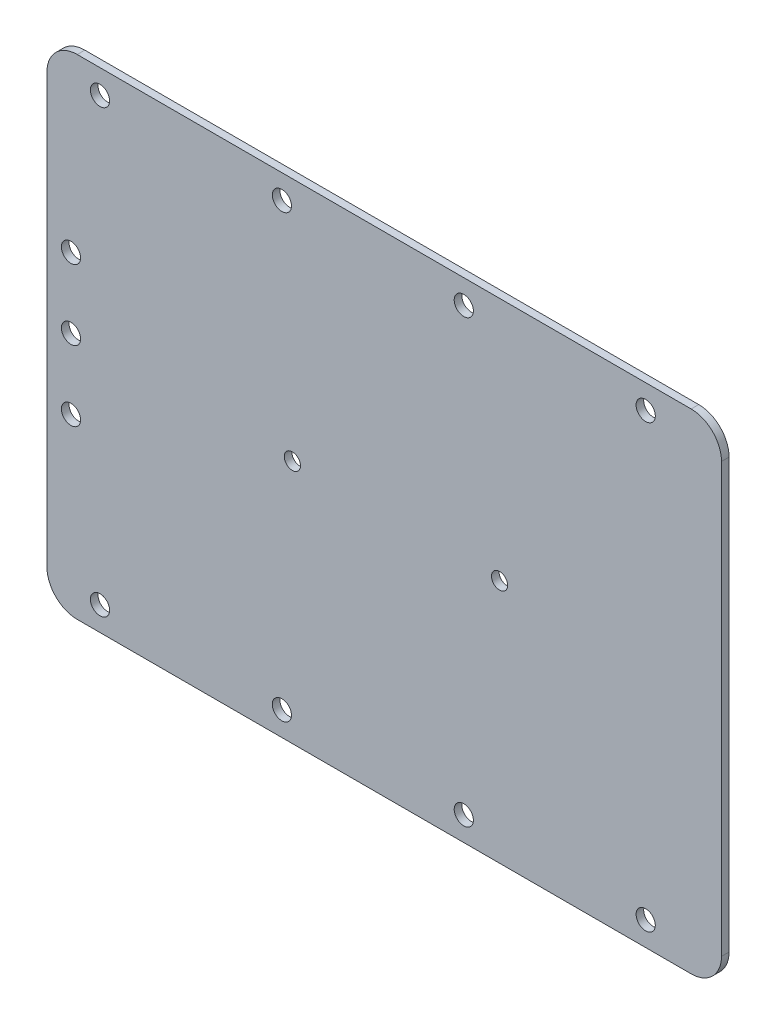
SolidWorks part; units mm, degrees
material "CNC Madness CF"
ref_plane "Front Plane" through (0, 0, 0) normal (0, 0, 1) x (1, 0, 0)
ref_plane "Top Plane" through (0, 0, 0) normal (0, 1, 0) x (1, 0, 0)
ref_plane "Right Plane" through (0, 0, 0) normal (1, 0, 0) x (0, 0, -1)
sketch "Sketch1" plane through (0, 0, 0) normal (0, 0, 1) x (1, 0, 0)
  line L0 (-83.9149, -87.3) -> (69.2267, -87.3) construction
  line L1 (-64.275, -77.775) -> (-64.275, 0) construction
  line L2 (-83.9149, 9.525) -> (69.2267, 9.525) construction
  line L3 (-83.9149, -87.3) -> (69.2267, -87.3) construction
  line L4 (-64.275, -77.775) -> (-64.275, 0) construction
  line L5 (-83.9149, 9.525) -> (69.2267, 9.525) construction
  line L7 (69.2267, 9.525) -> (-64.275, 9.525)
  line L8 (69.2267, 9.525) -> (69.2267, -87.3)
  line L9 (69.2267, -87.3) -> (-64.275, -87.3)
  line L10 (-64.275, 9.525) -> (-64.275, -87.3)
extrude "Boss-Extrude1" add sketch "Sketch1" along normal blind 1.5
ref_plane "Midplane" through (0, -38.8875, 0) normal (0, 1, 0) x (1, 0, 0)
sketch "Sketch3" plane through (0, 0, 1.5) normal (0, 0, 1) x (1, 0, 0)
  circle A0 centre (54.2267, 4.7625) radius 1.4732 construction
  circle A1 centre (54.2267, 4.7625) radius 1.4732 construction
  point P4 (54.2267, 4.7625)
hole_wizard "#6 Clearance Hole1" positions "Sketch4" profile "Sketch6" hole size "#6" standard "ANSI Inch" end condition through all
sketch "Sketch4" plane through (0, 0, 1.5) normal (0, 0, 1) x (1, 0, 0)
  point P0 (54.2267, 4.7625)
sketch "Sketch6" plane through (54.2267, 4.7625, 1.5) normal (1, 0, 0) x (0, -1, 0)
  line L0 (0, 0) -> (0, 1.5)
  line L1 (0, 1.5) -> (1.8986, 1.5)
  line L2 (1.8986, 1.5) -> (1.8986, 0)
  line L5 (1.8986, 0) -> (0, 0)
  line L11 (0, -6.35) -> (0, 107.95) construction
  dimension "Thru Hole Dia." = 3.7973
  dimension "Thru Hole Depth" = 1.5
pattern_linear "LPattern1" count 4 spacing 36 along (-1, 0, 0) of "#6 Clearance Hole1"
mirror "Mirror1" about plane through (0, -38.8875, 0) normal (0, 1, 0) of "LPattern1", "#6 Clearance Hole1"
sketch "Sketch7" plane through (0, 0, 1.5) normal (0, 0, 1) x (1, 0, 0)
  circle A0 centre (-59.5125, -52.775) radius 1.4732 construction
  circle A1 centre (-59.5125, -52.775) radius 1.4732 construction
  point P4 (-59.5125, -52.775)
hole_wizard "#6 Clearance Hole2" positions "Sketch8" profile "Sketch10" hole size "#6" standard "ANSI Inch" end condition through all
sketch "Sketch8" plane through (0, 0, 1.5) normal (0, 0, 1) x (1, 0, 0)
  point P0 (-59.5125, -52.775)
sketch "Sketch10" plane through (-59.5125, -52.775, 1.5) normal (1, 0, 0) x (0, -1, 0)
  line L0 (0, 0) -> (0, 1.5)
  line L1 (0, 1.5) -> (1.8986, 1.5)
  line L2 (1.8986, 1.5) -> (1.8986, 0)
  line L5 (1.8986, 0) -> (0, 0)
  line L11 (0, -6.35) -> (0, 107.95) construction
  dimension "Thru Hole Dia." = 3.7973
  dimension "Thru Hole Depth" = 1.5
pattern_linear "LPattern2" count 3 spacing 13.8875 along (0, 1, 0) of "#6 Clearance Hole2"
fillet "Fillet1" radius 6 4 edges at (-64.275, -87.3, 0.75) (69.2267, 9.525, 0.75) (69.2267, -87.3, 0.75) (-64.275, 9.525, 0.75)
sketch "Sketch11" plane through (0, 0, 0) normal (0, 0, -1) x (-1, 0, 0)
  circle A0 centre (15.6994, -38.8874) radius 1.8985 construction
  circle A1 centre (15.6994, -38.8874) radius 1.8985 construction
  circle A2 centre (-25.301, -38.8875) radius 1.8985 construction
  circle A3 centre (-25.301, -38.8875) radius 1.8985 construction
  circle A4 centre (-25.301, -38.8875) radius 1.6
  circle A5 centre (15.6994, -38.8874) radius 1.6
  dimension "D1" = 3.2
  dimension "D2" = 3.2
extrude "Cut-Extrude1" cut sketch "Sketch11" against normal through all
equation "\"D3@LPattern2\"=\"D3@Sketch4@P-0003-W - FRONT PANEL-1.Part\"/2"
equation "\"D3@LPattern1\"=\"bottom_sidepanel_hole_spacing@A-0000-N - ROOT LOCUS.Assembly\""
